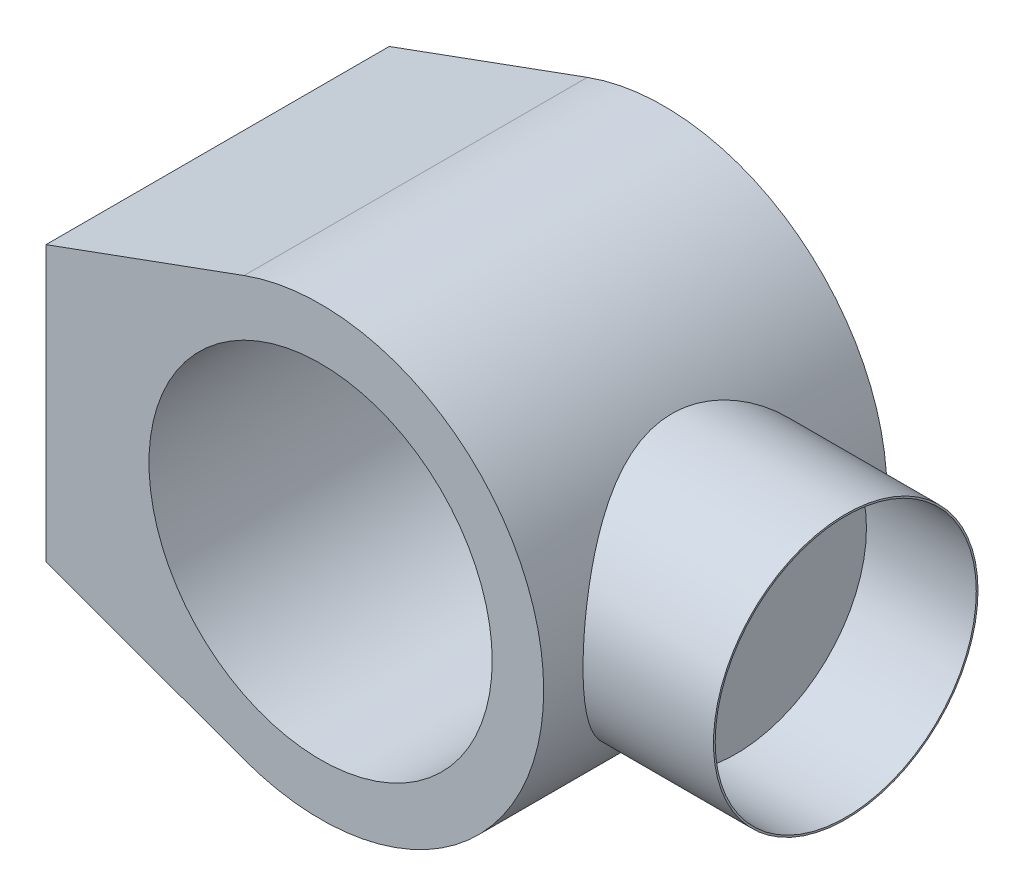
SolidWorks part; units mm, degrees
material "1023 Carbon Steel Sheet (SS)"
ref_plane "Front Plane" through (0, 0, 0) normal (0, 0, 1) x (1, 0, 0)
ref_plane "Top Plane" through (0, 0, 0) normal (0, 1, 0) x (1, 0, 0)
ref_plane "Right Plane" through (0, 0, 0) normal (1, 0, 0) x (0, 0, -1)
sketch "Sketch1" plane through (0, 0, 0) normal (0, 0, 1) x (1, 0, 0)
  line L0 (-80, 40) -> (-80, -40)
  line L1 (-80, 40) -> (-22.2817, 61.0617)
  line L2 (-80, -40) -> (-22.2817, -61.0617)
  arc A0 (-22.2817, -61.0617) -> (-22.2817, 61.0617) centre (0, 0) ccw
  circle A1 centre (0, 0) radius 50
  point P7 (-80, 0)
  dimension "D1" = 80
  dimension "D2" = 100
  dimension "D3" = 130
  dimension "D4" = 80
extrude "Boss-Extrude1" add sketch "Sketch1" along normal mid plane 100
ref_plane "Plane1" through (120, 0, 0) normal (1, 0, 0) x (0, 0, -1)
ref_plane "Plane2" through (103, 0, 0) normal (1, 0, 0) x (0, 0, -1)
sketch "Sketch2" plane through (103, 0, 0) normal (1, 0, 0) x (0, 0, -1)
  circle A0 centre (0, 0) radius 38.535
  circle A1 centre (0, 0) radius 38.035
  dimension "D1" = 77.07
  dimension "D2" = 76.07
extrude "Boss-Extrude2" add sketch "Sketch2" against normal up to next
sketch "Sketch3" plane through (103, 0, 0) normal (1, 0, 0) x (0, 0, -1)
  line L0 (15.724, -2.5) -> (8.724, 2.5) construction
  line L1 (1.5, 15.724) -> (-1.5, 15.724)
  line L2 (2.5, 14.724) -> (2.5, 9.724)
  line L3 (1.5, 8.724) -> (-1.5, 8.724)
  line L4 (-2.5, 14.724) -> (-2.5, 9.724)
  line L5 (2.5, 15.724) -> (-2.5, 8.724) construction
  line L6 (2.5, 8.724) -> (-2.5, 15.724) construction
  line L7 (8.724, -2.5) -> (15.724, 2.5) construction
  line L8 (14.724, -2.5) -> (9.724, -2.5)
  line L9 (15.724, -1.5) -> (15.724, 1.5)
  line L10 (14.724, 2.5) -> (9.724, 2.5)
  line L11 (8.724, -1.5) -> (8.724, 1.5)
  line L12 (-2.5, -15.724) -> (2.5, -8.724) construction
  line L13 (-2.5, -8.724) -> (2.5, -15.724) construction
  line L14 (-2.5, -14.724) -> (-2.5, -9.724)
  line L15 (-1.5, -15.724) -> (1.5, -15.724)
  line L16 (2.5, -14.724) -> (2.5, -9.724)
  line L17 (-1.5, -8.724) -> (1.5, -8.724)
  line L18 (-15.724, 2.5) -> (-8.724, -2.5) construction
  line L19 (-8.724, 2.5) -> (-15.724, -2.5) construction
  line L20 (-14.724, 2.5) -> (-9.724, 2.5)
  line L21 (-15.724, 1.5) -> (-15.724, -1.5)
  line L22 (-14.724, -2.5) -> (-9.724, -2.5)
  line L23 (-8.724, 1.5) -> (-8.724, -1.5)
  arc A0 (-2.5, -9.724) -> (-1.5, -8.724) centre (-1.5, -9.724) cw
  arc A1 (-1.5, -15.724) -> (-2.5, -14.724) centre (-1.5, -14.724) cw
  arc A2 (2.5, -14.724) -> (1.5, -15.724) centre (1.5, -14.724) cw
  arc A3 (2.5, -9.724) -> (1.5, -8.724) centre (1.5, -9.724) ccw
  arc A4 (-15.724, 1.5) -> (-14.724, 2.5) centre (-14.724, 1.5) cw
  arc A5 (-14.724, -2.5) -> (-15.724, -1.5) centre (-14.724, -1.5) cw
  arc A6 (-8.724, -1.5) -> (-9.724, -2.5) centre (-9.724, -1.5) cw
  arc A7 (-9.724, 2.5) -> (-8.724, 1.5) centre (-9.724, 1.5) cw
  arc A8 (8.724, 1.5) -> (9.724, 2.5) centre (9.724, 1.5) cw
  arc A9 (9.724, -2.5) -> (8.724, -1.5) centre (9.724, -1.5) cw
  arc A10 (15.724, -1.5) -> (14.724, -2.5) centre (14.724, -1.5) cw
  arc A11 (15.724, 1.5) -> (14.724, 2.5) centre (14.724, 1.5) ccw
  arc A12 (-2.5, 14.724) -> (-1.5, 15.724) centre (-1.5, 14.724) cw
  arc A13 (-1.5, 8.724) -> (-2.5, 9.724) centre (-1.5, 9.724) cw
  arc A14 (2.5, 9.724) -> (1.5, 8.724) centre (1.5, 9.724) cw
  arc A15 (2.5, 14.724) -> (1.5, 15.724) centre (1.5, 14.724) ccw
  point P0 (0, 12.224)
  point P5 (-7.0142, 5.8339)
  point P10 (-19.2382, -6.3901)
  point P19 (0, 0)
  dimension "D7" = 1
  dimension "D1" = 7
  dimension "D2" = 5
  dimension "D3" = 8.724
  dimension "D4" = 17.448
  dimension "D5" = 17.448
  dimension "D6" = 8.724
curve "Curve1"
ref_plane "Plane3" through (68, 0, 0) normal (1, 0, 0) x (0, 0, -1)
sketch "Sketch4" plane through (68, 0, 0) normal (1, 0, 0) x (0, 0, -1)
  circle A0 centre (0, 0) radius 38.035
extrude "Boss-Extrude3" add sketch "Sketch4" along normal blind 3
